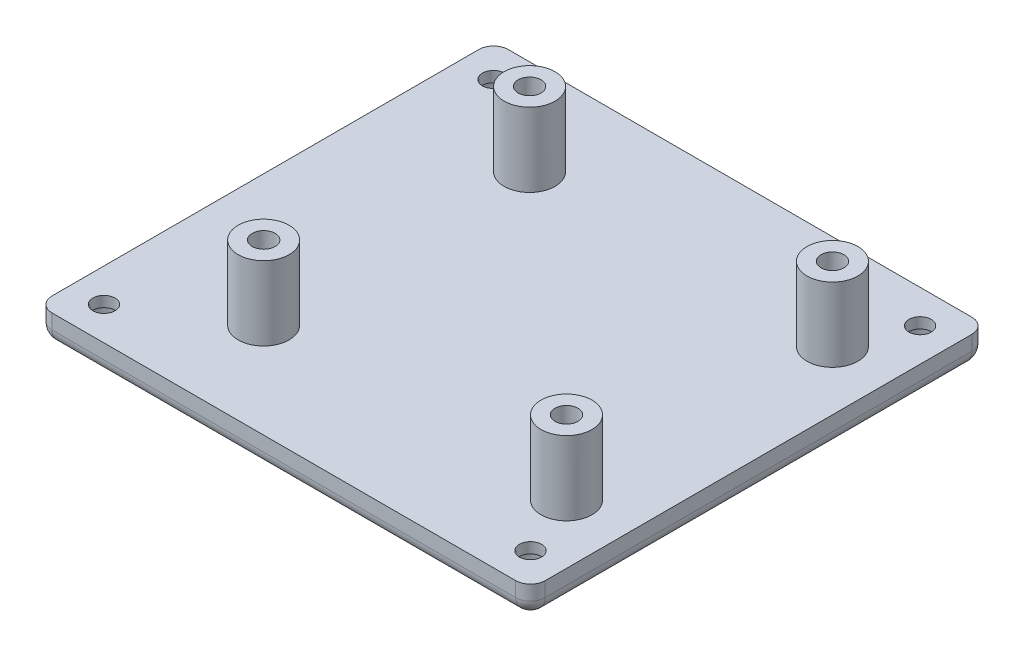
SolidWorks part; units mm, degrees
ref_plane "Front Plane" through (0, 0, 0) normal (0, 0, 1) x (1, 0, 0)
ref_plane "Top Plane" through (0, 0, 0) normal (0, 1, 0) x (1, 0, 0)
ref_plane "Right Plane" through (0, 0, 0) normal (1, 0, 0) x (0, 0, -1)
sketch "Sketch1" plane through (0, 0, 0) normal (0, 1, 0) x (1, 0, 0)
  line L1 (0, 0) -> (66.76, 0)
  line L2 (0, 0) -> (0, 61.76)
  line L3 (0, 61.76) -> (66.76, 61.76)
  line L4 (66.76, 0) -> (66.76, 61.76)
  dimension "D1" = 66.76
  dimension "D2" = 61.76
extrude "Boss-Extrude3" add sketch "Sketch1" against normal blind 4
sketch "Sketch2" plane through (0, 0, 0) normal (0, 1, 0) x (1, 0, 0)
  line L0 (62.76, 8.88) -> (13.76, 8.88) construction
  line L1 (0, 61.76) -> (0, 0) construction
  line L2 (17.76, 12.88) -> (58.76, 12.88) construction
  line L3 (0, 0) -> (66.76, 0) construction
  line L4 (66.76, 0) -> (66.76, 61.76) construction
  line L5 (66.76, 61.76) -> (0, 61.76) construction
  line L6 (62.76, 59.75) -> (62.76, 2.01) construction
  line L7 (2.01, 2.01) -> (64.75, 2.01) construction
  line L8 (2.01, 2.01) -> (2.01, 59.75) construction
  line L9 (2.01, 59.75) -> (64.75, 59.75) construction
  line L10 (64.75, 2.01) -> (64.75, 59.75) construction
  line L11 (17.76, 12.88) -> (17.76, 48.88) construction
  line L12 (17.76, 48.88) -> (58.76, 48.88) construction
  line L13 (58.76, 12.88) -> (58.76, 48.88) construction
  line L14 (13.76, 8.88) -> (13.76, 52.88) construction
  line L15 (13.76, 52.88) -> (62.76, 52.88) construction
  line L16 (0, 30.88) -> (66.76, 30.88) construction
  line L17 (38.26, 12.88) -> (38.26, 48.88) construction
  circle A0 centre (58.76, 12.88) radius 1.55
  circle A4 centre (58.76, 12.88) radius 3.45
  circle A5 centre (17.76, 12.88) radius 3.45
  circle A6 centre (17.76, 12.88) radius 1.55
  circle A7 centre (17.76, 48.88) radius 1.55
  circle A8 centre (58.76, 48.88) radius 1.55
  circle A9 centre (58.76, 48.88) radius 3.45
  circle A10 centre (17.76, 48.88) radius 3.45
  arc A11 (55.76, 2.01) -> (62.76, 9.01) centre (62.76, 2.01) cw construction
  dimension "D13" = 3.1
  dimension "D11" = 6.9
  dimension "D14" = 7
  dimension "D1" = 2.01
  dimension "D2" = 2.01
  dimension "D3" = 1.99
  dimension "D4" = 2.01
  dimension "D5" = 2.01
  dimension "D6" = 49
  dimension "D7" = 44
  dimension "D8" = 22
  dimension "D9" = 4
  dimension "D10" = 4
  dimension "D12" = 4
extrude "Boss-Extrude4" add sketch "Sketch2" along normal blind 10
sketch "Sketch3" plane through (0, 0, 0) normal (0, 1, 0) x (1, 0, 0)
  line L0 (0, 61.76) -> (0, 0) construction
  line L1 (33.38, 59.75) -> (33.38, 2.01) construction
  line L2 (2.01, 30.88) -> (64.75, 30.88) construction
  line L3 (2.01, 59.75) -> (64.75, 59.75) construction
  line L6 (2.01, 59.75) -> (2.01, 2.01) construction
  line L11 (2.01, 2.01) -> (64.75, 2.01) construction
  line L12 (64.75, 59.75) -> (64.75, 2.01) construction
  line L13 (0, 0) -> (66.76, 0) construction
  line L14 (66.76, 61.76) -> (0, 61.76) construction
  line L15 (66.76, 0) -> (66.76, 61.76) construction
  circle A0 centre (4.51, 57.25) radius 1.5
  circle A1 centre (62.25, 57.25) radius 1.5
  circle A2 centre (62.25, 4.51) radius 1.5
  circle A3 centre (4.51, 4.51) radius 1.5
  dimension "D5" = 3
  dimension "D1" = 2.01
  dimension "D2" = 2.01
  dimension "D3" = 2.01
  dimension "D4" = 2.01
  dimension "D6" = 2.5
  dimension "D7" = 2.5
extrude "Cut-Extrude1" cut sketch "Sketch3" against normal blind 3 draft 3 draft outward yes
sketch "Sketch5" plane through (0, -4, 0) normal (0, -1, 0) x (1, 0, 0)
  line L0 (33.38, -4.51) -> (33.38, -57.6662) construction
  line L1 (4.51, -4.51) -> (62.25, -4.51) construction
  line L2 (4.51, -4.51) -> (4.51, -57.25) construction
  line L3 (4.51, -57.25) -> (62.25, -57.25) construction
  line L4 (62.25, -4.51) -> (62.25, -57.25) construction
  line L5 (4.51, -30.88) -> (62.25, -30.88) construction
  circle A0 centre (4.51, -4.51) radius 3.15
  circle A1 centre (62.25, -4.51) radius 3.15
  circle A2 centre (62.25, -57.25) radius 3.15
  circle A3 centre (4.51, -57.25) radius 3.15
  point P10 (33.38, -30.88)
  dimension "D1" = 6.3
fillet "Fillet2" radius 2 4 edges at (0, -2, 0) (66.76, -2, 0) (66.76, -2, -61.76) (0, -2, -61.76)
fillet "Fillet1" radius 2 8 edges at (66.76, -4, -30.88) (33.38, -4, -61.76) (0, -4, -30.88) (33.38, -4, 0) (0.5858, -4, -0.5858) (0.5858, -4, -61.1742) (66.1742, -4, -61.1742) (66.1742, -4, -0.5858)
extrude "Cut-Extrude2" cut sketch "Sketch5" against normal blind 2.5 draft 1
